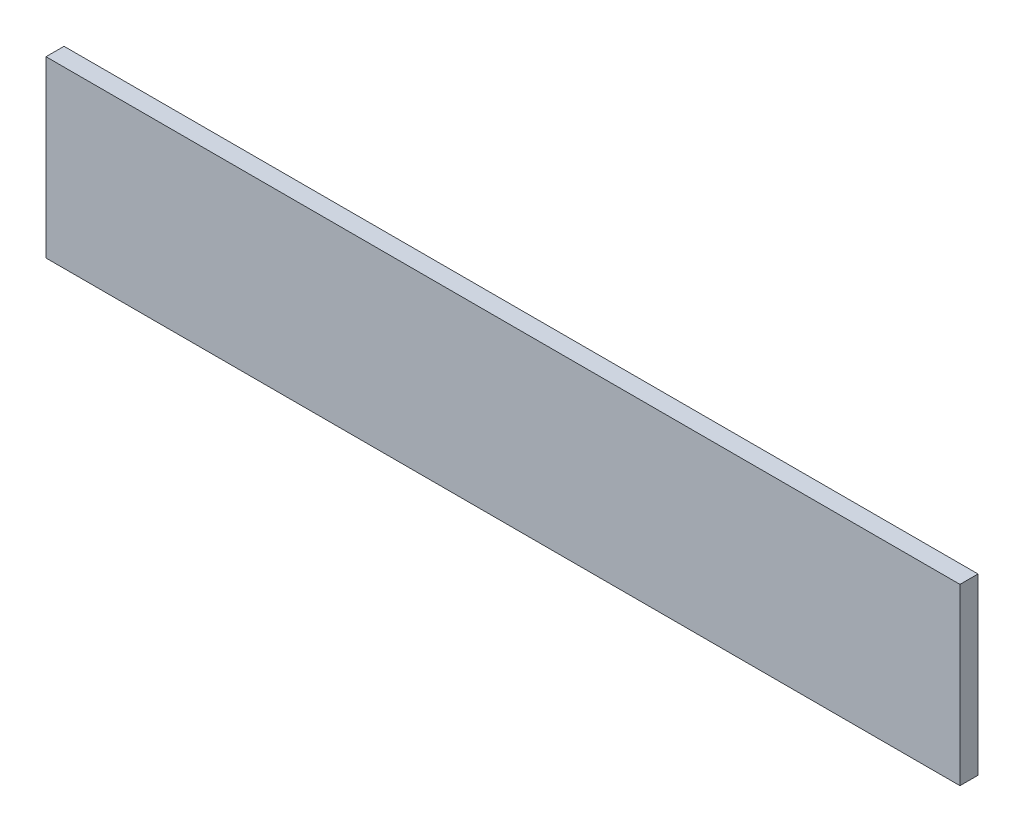
SolidWorks part; units mm, degrees
ref_plane "Front Plane" through (0, 0, 0) normal (0, 0, 1) x (1, 0, 0)
ref_plane "Top Plane" through (0, 0, 0) normal (0, 1, 0) x (1, 0, 0)
ref_plane "Right Plane" through (0, 0, 0) normal (1, 0, 0) x (0, 0, -1)
sketch "Sketch1" plane through (0, 0, 0) normal (0, 0, 1) x (1, 0, 0)
  line L1 (0, 0) -> (965.2, 0)
  line L2 (0, 0) -> (0, 184.15)
  line L3 (0, 184.15) -> (965.2, 184.15)
  line L4 (965.2, 0) -> (965.2, 184.15)
  dimension "D1" = 965.2
  dimension "D2" = 184.15
extrude "Boss-Extrude1" add sketch "Sketch1" along normal blind 19.05
